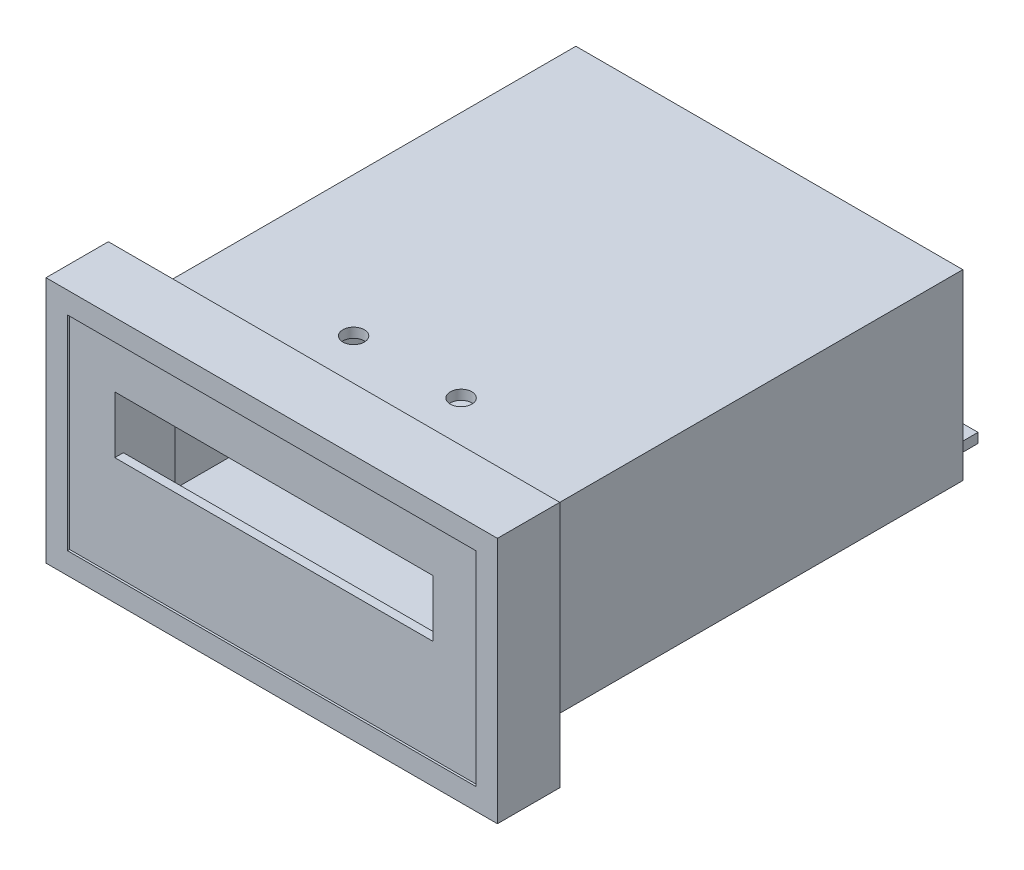
SolidWorks part; units mm, degrees
ref_plane "Front Plane" through (0, 0, 0) normal (0, 0, 1) x (1, 0, 0)
ref_plane "Top Plane" through (0, 0, 0) normal (0, 1, 0) x (1, 0, 0)
ref_plane "Right Plane" through (0, 0, 0) normal (1, 0, 0) x (0, 0, -1)
sketch "Sketch1" plane through (0, 0, 0) normal (0, 0, 1) x (1, 0, 0)
  line L0 (0, 0) -> (-53.34, 0) construction
  line L1 (-53.34, 0) -> (-53.34, 29.21) construction
  line L2 (-53.34, 29.21) -> (53.34, 29.21)
  line L3 (53.34, 29.21) -> (53.34, -29.21)
  line L4 (53.34, -29.21) -> (-53.34, -29.21)
  line L5 (-53.34, -29.21) -> (-53.34, 29.21)
  dimension "D1" = 53.34
  dimension "D2" = 29.21
  dimension "D3" = 106.68
  dimension "D4" = 58.42
extrude "Boss-Extrude1" add sketch "Sketch1" against normal blind 14.732
sketch "Sketch2" plane through (0, 0, 0) normal (0, 0, 1) x (1, 0, 0)
  line L8 (-48.26, -24.13) -> (48.26, -24.13)
  line L9 (48.26, -24.13) -> (48.26, 24.13)
  line L10 (48.26, 24.13) -> (-48.26, 24.13)
  line L11 (-48.26, 24.13) -> (-48.26, -24.13)
  line L12 (-53.34, 29.21) -> (-53.34, -29.21) construction
  line L13 (-53.34, -29.21) -> (53.34, -29.21) construction
  dimension "D1" = 5.08
  dimension "D2" = 101.6
  dimension "D3" = 5.08
  dimension "D4" = 53.34
extrude "Cut-Extrude1" cut sketch "Sketch2" against normal blind 0.508
sketch "Sketch3" plane through (0, 0, -14.732) normal (0, 0, -1) x (-1, 0, 0)
  line L8 (37.592, 13.462) -> (37.592, -13.462)
  line L9 (37.592, -13.462) -> (-37.592, -13.462)
  line L10 (-37.592, -13.462) -> (-37.592, 13.462)
  line L11 (-37.592, 13.462) -> (37.592, 13.462)
  line L12 (53.34, 29.21) -> (53.34, -29.21) construction
  line L13 (-53.34, 29.21) -> (53.34, 29.21) construction
  dimension "D1" = 15.748
  dimension "D2" = 90.932
  dimension "D3" = 15.748
  dimension "D4" = 42.672
extrude "Cut-Extrude2" cut sketch "Sketch3" against normal blind 12.192
sketch "Sketch4" plane through (0, 0, -2.54) normal (0, 0, -1) x (-1, 0, 0)
  line L0 (-37.592, 13.462) -> (37.592, 13.462)
  line L1 (37.592, 13.462) -> (37.592, 0)
  line L2 (37.592, -13.462) -> (37.592, 13.462) construction
  line L3 (37.592, 0) -> (-37.592, 0)
  line L4 (-37.592, 13.462) -> (-37.592, -13.462) construction
  line L5 (-37.592, 0) -> (-37.592, 13.462)
extrude "Cut-Extrude3" cut sketch "Sketch4" against normal blind 12.192
sketch "Sketch5" plane through (0, 0, -14.732) normal (0, 0, -1) x (-1, 0, 0)
  line L8 (48.26, -24.13) -> (-48.26, -24.13)
  line L9 (-48.26, -24.13) -> (-48.26, 24.13)
  line L10 (-48.26, 24.13) -> (48.26, 24.13)
  line L11 (48.26, 24.13) -> (48.26, -24.13)
  line L12 (-37.592, 13.462) -> (-37.592, -13.462) construction
  line L13 (37.592, 13.462) -> (-37.592, 13.462) construction
  line L14 (45.72, -21.59) -> (-45.72, -21.59)
  line L15 (-45.72, -21.59) -> (-45.72, 21.59)
  line L16 (-45.72, 21.59) -> (45.72, 21.59)
  line L17 (45.72, 21.59) -> (45.72, -21.59)
  dimension "D1" = 85.852
  dimension "D2" = 10.668
  dimension "D3" = 10.668
  dimension "D4" = 37.592
  dimension "D5" = 2.54
extrude "Boss-Extrude2" add sketch "Sketch5" along normal blind 3.81
sketch "Sketch6" plane through (0, 0, -18.542) normal (0, 0, -1) x (-1, 0, 0)
  line L0 (-45.72, 21.59) -> (-45.72, -21.59)
  line L1 (-45.72, -21.59) -> (45.72, -21.59)
  line L2 (45.72, -21.59) -> (45.72, 21.59)
  line L3 (45.72, 21.59) -> (-45.72, 21.59)
  line L4 (-43.434, 19.304) -> (-43.434, -19.304)
  line L5 (-43.434, -19.304) -> (43.434, -19.304)
  line L6 (43.434, -19.304) -> (43.434, 19.304)
  line L7 (43.434, 19.304) -> (-43.434, 19.304)
  dimension "D1" = 2.286
extrude "Boss-Extrude3" add sketch "Sketch6" along normal blind 99.06 separate body
sketch "Sketch7" plane through (0, 0, -117.602) normal (0, 0, -1) x (-1, 0, 0)
  line L0 (0, 0) -> (43.434, 0) construction
  line L1 (43.434, -19.304) -> (43.434, 19.304) construction
  line L2 (43.434, 0) -> (43.434, 5.08) construction
  line L3 (43.434, 5.08) -> (-43.434, 5.08)
  line L4 (-43.434, 19.304) -> (-43.434, -19.304) construction
  line L5 (-43.434, 5.08) -> (-43.434, -5.08)
  line L6 (-43.434, -5.08) -> (43.434, -5.08)
  line L7 (43.434, -5.08) -> (43.434, 5.08)
  dimension "D1" = 5.08
  dimension "D2" = 10.16
extrude "Boss-Extrude4" add sketch "Sketch7" against normal blind 2.54
sketch "Sketch8" plane through (0, -19.304, 0) normal (0, 1, 0) x (1, 0, 0)
  line L0 (-43.434, 117.602) -> (-38.354, 117.602) construction
  line L1 (43.434, 117.602) -> (-43.434, 117.602) construction
  line L2 (-38.354, 117.602) -> (-38.354, 126.9901)
  line L3 (-38.354, 126.9901) -> (39.9204, 126.9901)
  line L4 (39.9204, 126.9901) -> (39.9204, 117.602)
  line L5 (39.9204, 117.602) -> (-38.354, 117.602)
  line L6 (43.434, 117.602) -> (43.434, 18.542) construction
  line L7 (43.434, 18.542) -> (-43.434, 18.542) construction
  dimension "D1" = 5.08
  dimension "D2" = 3.5136
  dimension "D3" = 108.4481
extrude "Boss-Extrude5" add sketch "Sketch8" against normal blind 2.286
sketch "Sketch9" plane through (0, 21.59, 0) normal (0, 1, 0) x (1, 0, 0)
  line L0 (45.72, 117.602) -> (45.72, 18.542) construction
  line L1 (53.34, 14.732) -> (-53.34, 14.732) construction
  circle A0 centre (12.7, 32.0548) radius 2.54
  circle A1 centre (-12.7, 32.0548) radius 2.54
  dimension "D4" = 5.08
  dimension "D1" = 25.4
  dimension "D2" = 33.02
  dimension "D3" = 17.3228
extrude "Cut-Extrude4" cut sketch "Sketch9" against normal up to surface (2.286 mm away) up to face at (0, 19.304, -68.072)
